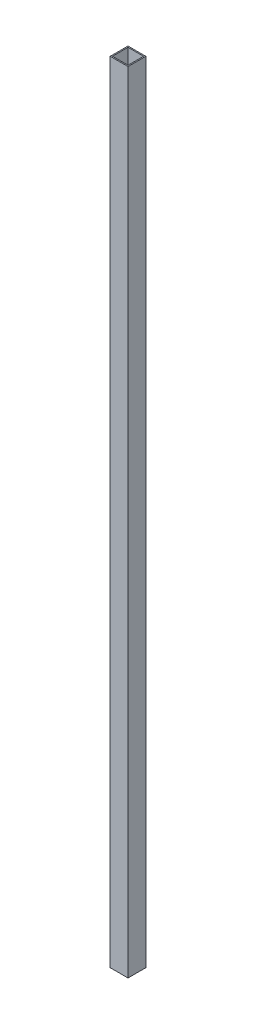
SolidWorks part; units mm, degrees
ref_plane "Front Plane" through (0, 0, 0) normal (0, 0, 1) x (1, 0, 0)
ref_plane "Top Plane" through (0, 0, 0) normal (0, 1, 0) x (1, 0, 0)
ref_plane "Right Plane" through (0, 0, 0) normal (1, 0, 0) x (0, 0, -1)
sketch "Sketch1" plane through (0, 0, 0) normal (0, 1, 0) x (1, 0, 0)
  line L1 (-25.4, 25.4) -> (25.4, 25.4)
  line L2 (-25.4, 25.4) -> (-25.4, -25.4)
  line L3 (-25.4, -25.4) -> (25.4, -25.4)
  line L4 (25.4, 25.4) -> (25.4, -25.4)
  line L5 (-25.4, 25.4) -> (25.4, -25.4) construction
  line L6 (-25.4, -25.4) -> (25.4, 25.4) construction
  line L7 (-22.225, 22.225) -> (22.225, 22.225)
  line L8 (-22.225, 22.225) -> (-22.225, -22.225)
  line L9 (-22.225, -22.225) -> (22.225, -22.225)
  line L10 (22.225, 22.225) -> (22.225, -22.225)
  line L11 (-22.225, 22.225) -> (22.225, -22.225) construction
  line L12 (-22.225, -22.225) -> (22.225, 22.225) construction
  point P0 (0, 0)
  point P6 (0, 0)
  dimension "D1" = 50.8
  dimension "D2" = 3.175
extrude "Boss-Extrude1" add sketch "Sketch1" along normal blind 2254.25
